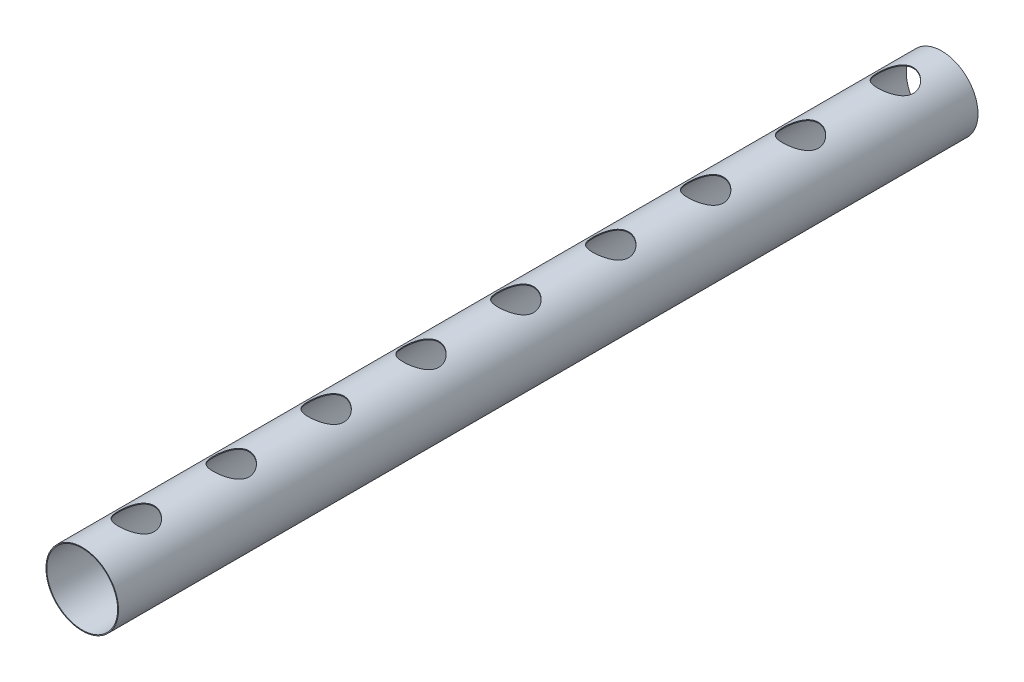
SolidWorks part; units mm, degrees
ref_plane "정면" through (0, 0, 0) normal (0, 0, 1) x (1, 0, 0)
ref_plane "윗면" through (0, 0, 0) normal (0, 1, 0) x (1, 0, 0)
ref_plane "우측면" through (0, 0, 0) normal (1, 0, 0) x (0, 0, -1)
sketch "스케치1" plane through (0, 0, 0) normal (0, 0, 1) x (1, 0, 0)
  circle A0 centre (0, 0) radius 32.5
  circle A1 centre (0, 0) radius 31.75
  dimension "D1" = 65
  dimension "D2" = 63.5
extrude "보스-돌출1" add sketch "스케치1" along normal blind 770
sketch "스케치2" plane through (0, 0, 0) normal (0, 1, 0) x (1, 0, 0)
  line L0 (0, 0) -> (0, -770) construction
  line L1 (-32.5, -770) -> (32.5, -770) construction
  circle A0 centre (0, -41.5) radius 16
  dimension "D1" = 32
  dimension "D2" = 41.5
extrude "컷-돌출1" cut sketch "스케치2" along normal up to next
pattern_linear "선형 패턴1" count 9 spacing 85 along (0, 0, 1) of "컷-돌출1"
